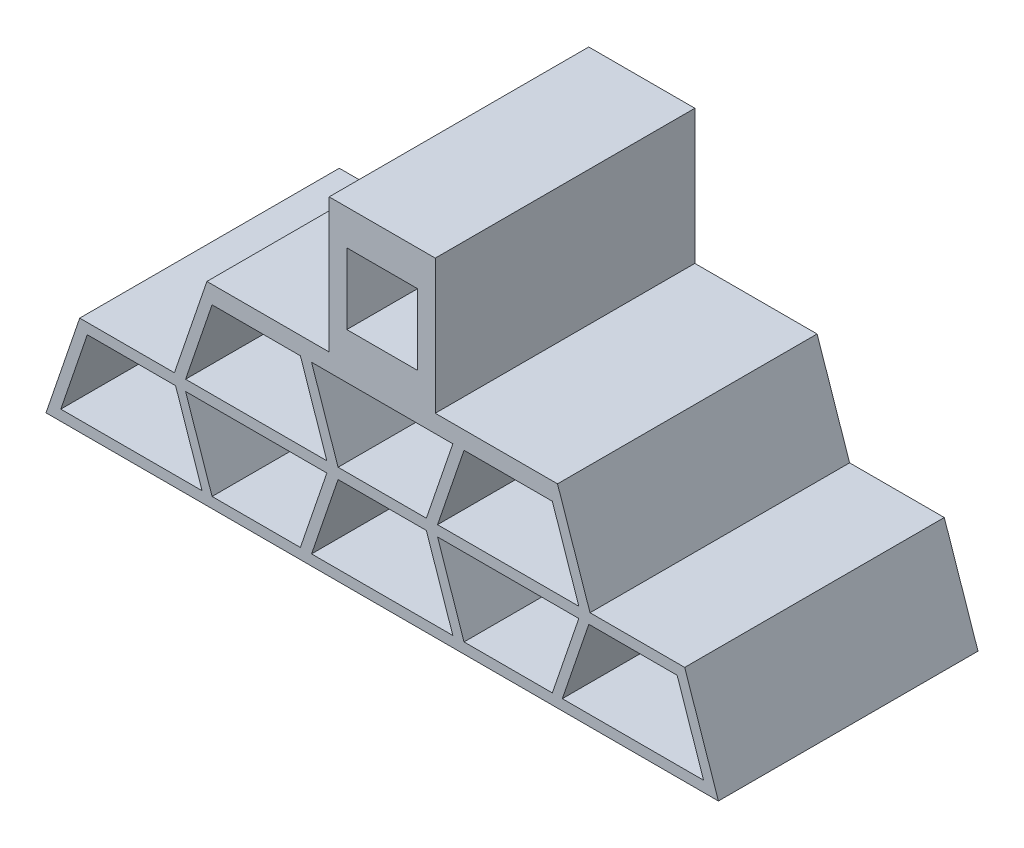
SolidWorks part; units mm, degrees
ref_plane "Front Plane" through (0, 0, 0) normal (0, 0, 1) x (1, 0, 0)
ref_plane "Top Plane" through (0, 0, 0) normal (0, 1, 0) x (1, 0, 0)
ref_plane "Right Plane" through (0, 0, 0) normal (1, 0, 0) x (0, 0, -1)
sketch "Sketch1" plane through (0, 0, 0) normal (0, 0, 1) x (1, 0, 0)
  line L0 (0, 45.5072) -> (0, -93.928) construction
  line L1 (-48.8406, 0) -> (45.7971, 0) construction
  line L3 (10.0225, -10.0225) -> (-10.0225, -10.0225)
  line L4 (10.0225, -10.0225) -> (10.0225, 10.0225)
  line L5 (10.0225, 10.0225) -> (-10.0225, 10.0225)
  line L6 (-10.0225, -10.0225) -> (-10.0225, 10.0225)
  line L7 (10.0225, -10.0225) -> (-10.0225, 10.0225) construction
  line L8 (10.0225, 10.0225) -> (-10.0225, -10.0225) construction
  line L18 (-20, -23.0225) -> (20, -23.0225)
  line L19 (20, -23.0225) -> (12.5, -45.0225)
  line L20 (-12.5, -45.0225) -> (12.5, -45.0225)
  line L21 (-20, -23.0225) -> (-12.5, -45.0225)
  line L53 (-68.8906, -46.5225) -> (82.3057, -46.5225) construction
  line L76 (-62.7657, -20) -> (65.3674, -20) construction
  line L108 (23.1695, -23.0225) -> (15.6695, -45.0225)
  line L116 (15.6695, -45.0225) -> (55.6695, -45.0225)
  line L117 (55.6695, -45.0225) -> (48.1695, -23.0225)
  line L118 (48.1695, -23.0225) -> (23.1695, -23.0225)
  line L119 (35.6695, -99.2694) -> (35.6695, -13.2069) construction
  line L120 (-55.6695, -45.0225) -> (-48.1695, -23.0225)
  line L121 (-15.6695, -45.0225) -> (-55.6695, -45.0225)
  line L122 (-23.1695, -23.0225) -> (-15.6695, -45.0225)
  line L123 (-48.1695, -23.0225) -> (-23.1695, -23.0225)
  line L140 (55.6695, -48.0225) -> (48.1695, -70.0225)
  line L141 (15.6695, -48.0225) -> (55.6695, -48.0225)
  line L142 (23.1695, -70.0225) -> (15.6695, -48.0225)
  line L143 (48.1695, -70.0225) -> (23.1695, -70.0225)
  line L144 (-20, -70.0225) -> (-12.5, -48.0225)
  line L145 (-12.5, -48.0225) -> (12.5, -48.0225)
  line L146 (20, -70.0225) -> (12.5, -48.0225)
  line L147 (-20, -70.0225) -> (20, -70.0225)
  line L148 (-15.6695, -48.0225) -> (-55.6695, -48.0225)
  line L149 (-23.1695, -70.0225) -> (-15.6695, -48.0225)
  line L150 (-48.1695, -70.0225) -> (-23.1695, -70.0225)
  line L151 (-55.6695, -48.0225) -> (-48.1695, -70.0225)
  line L160 (51, -70.0225) -> (58.5, -48.0225)
  line L161 (58.5, -48.0225) -> (83.5, -48.0225)
  line L162 (91, -70.0225) -> (83.5, -48.0225)
  line L163 (51, -70.0225) -> (91, -70.0225)
  line L164 (-91, -70.0225) -> (-83.5, -48.0225)
  line L165 (-83.5, -48.0225) -> (-58.5, -48.0225)
  line L166 (-51, -70.0225) -> (-58.5, -48.0225)
  line L167 (-91, -70.0225) -> (-51, -70.0225)
  line L168 (-95.1923, -73.0225) -> (95.1923, -73.0225)
  line L169 (-95.1923, -73.0225) -> (-85.6468, -45.0225)
  line L173 (-85.6468, -45.0225) -> (-56.3532, -45.0225) construction
  line L174 (-46.8077, -73.0225) -> (-56.3532, -45.0225) construction
  line L175 (-95.1923, -73.0225) -> (-46.8077, -73.0225) construction
  line L176 (-85.6468, -45.0225) -> (-58.8391, -45.0225)
  line L177 (15.0225, 20.0225) -> (-15.0225, 20.0225)
  line L178 (-15.0225, 20.0225) -> (-15.0225, -18.0225)
  line L179 (-15.0225, -18.0225) -> (-49.6345, -18.0225)
  line L180 (-49.6345, -18.0225) -> (-58.8391, -45.0225)
  line L181 (95.1923, -73.0225) -> (85.6468, -45.0225)
  line L182 (85.6468, -45.0225) -> (58.8391, -45.0225)
  line L183 (49.6345, -18.0225) -> (58.8391, -45.0225)
  line L184 (15.0225, -18.0225) -> (49.6345, -18.0225)
  line L185 (15.0225, 20.0225) -> (15.0225, -18.0225)
  point P5 (0, 0)
  point P10 (0, 0)
  point P11 (-48.0225, -34.6468)
  point P12 (-24.1923, -85.0225)
  point P13 (0, 14)
  point P14 (0, 35)
  point P15 (24.1923, -85.0225)
  point P16 (22.4772, 38)
  point P17 (14.6468, -57.0225)
  point P18 (-22.4772, 38)
  point P19 (0, 35)
  point P20 (-14.7629, 11)
  point P21 (-20.0225, -44.1923)
  point P33 (14.7629, 11)
  point P56 (-59.8618, -35.0225)
  point P57 (-50.3163, -63.0225)
  point P74 (0, -73.0225)
  point P79 (0, 20.0225)
  dimension "D1" = 20.045
  dimension "D2" = 20.045
  dimension "D3" = 40
  dimension "D4" = 25
  dimension "D5" = 22
  dimension "D6" = 1.5
  dimension "D8" = 13
  dimension "D9" = 12.5
  dimension "D10" = 40
  dimension "D11" = 25
  dimension "D7" = 20
  dimension "D13" = 3
  dimension "D14" = 13
  dimension "D15" = 12.5
  dimension "D16" = 20
  dimension "D17" = 2
  dimension "D18" = 2
  dimension "D19" = 10
  dimension "D22" = 5
  dimension "D12" = 22
  dimension "D20" = 3
  dimension "D21" = 5
  dimension "D23" = 3
extrude "Boss-Extrude1" add sketch "Sketch1" along normal blind 73.5
